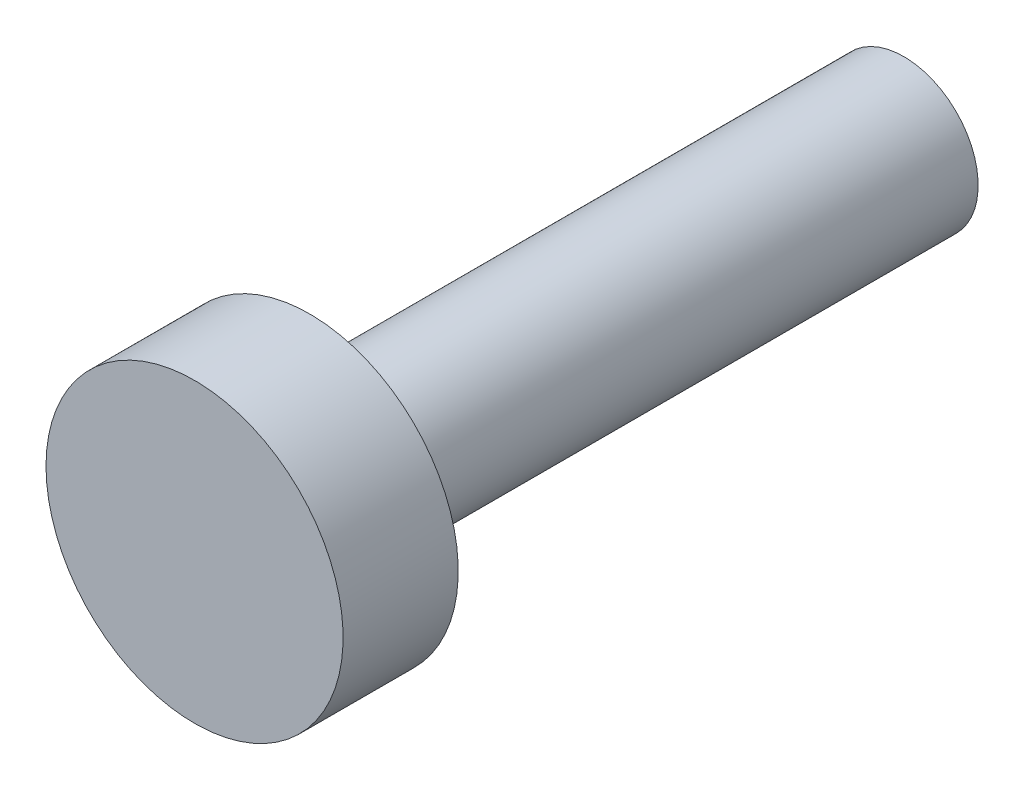
SolidWorks part; units mm, degrees
ref_plane "Plan de face" through (0, 0, 0) normal (0, 0, 1) x (1, 0, 0)
ref_plane "Plan de dessus" through (0, 0, 0) normal (0, 1, 0) x (1, 0, 0)
ref_plane "Plan de droite" through (0, 0, 0) normal (1, 0, 0) x (0, 0, -1)
sketch "Esquisse1" plane through (0, 0, 0) normal (0, 0, 1) x (1, 0, 0)
  circle A0 centre (0, 0) radius 4
  dimension "D1" = 8
extrude "Boss.-Extru.1" add sketch "Esquisse1" along normal blind 3.1
sketch "Esquisse2" plane through (0, 0, 0) normal (0, 0, -1) x (-1, 0, 0)
  circle A0 centre (0, 0) radius 2
  dimension "D1" = 4
extrude "Boss.-Extru.2" add sketch "Esquisse2" along normal blind 16
